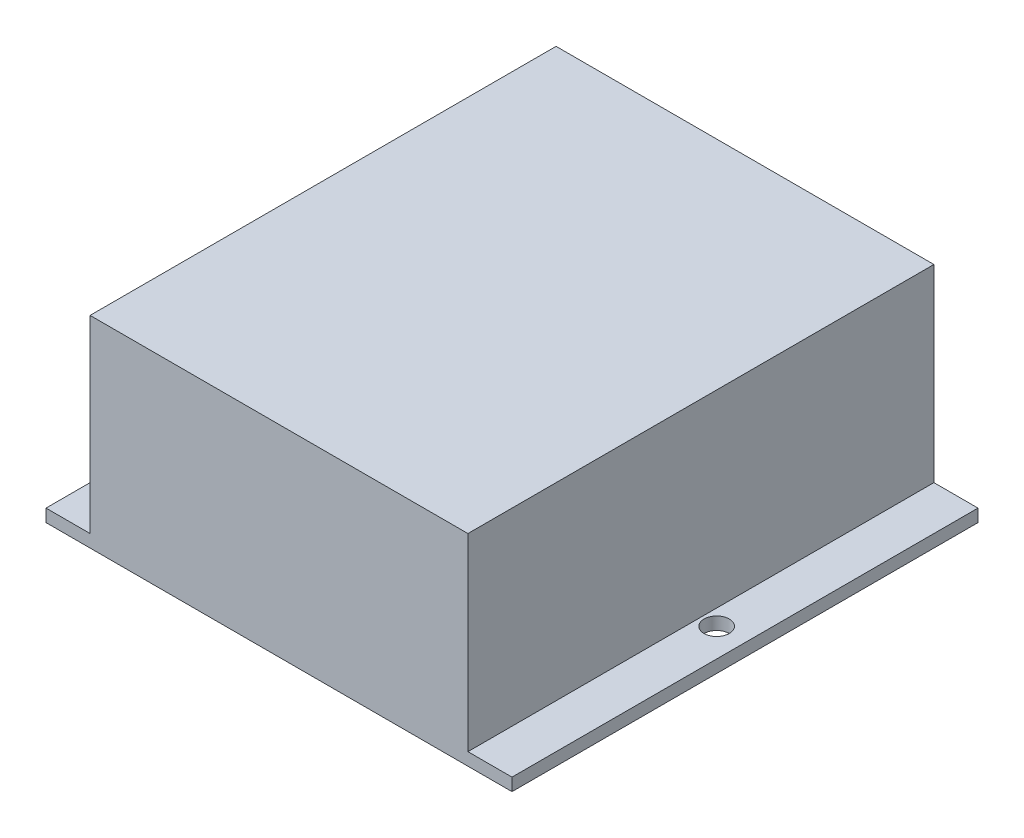
SolidWorks part; units mm, degrees
ref_plane "Front Plane" through (0, 0, 0) normal (0, 0, 1) x (1, 0, 0)
ref_plane "Top Plane" through (0, 0, 0) normal (0, 1, 0) x (1, 0, 0)
ref_plane "Right Plane" through (0, 0, 0) normal (1, 0, 0) x (0, 0, -1)
sketch "Sketch1" plane through (0, 0, 0) normal (0, 1, 0) x (1, 0, 0)
  line L1 (0, 0) -> (74, 0)
  line L2 (0, 0) -> (0, 74)
  line L3 (0, 74) -> (74, 74)
  line L4 (74, 0) -> (74, 74)
  dimension "D1" = 74
  dimension "D2" = 74
extrude "Boss-Extrude1" add sketch "Sketch1" along normal blind 2
sketch "Sketch2" plane through (0, 2, 0) normal (0, 1, 0) x (1, 0, 0)
  line L0 (37, 74) -> (37, 0) construction
  line L1 (74, 74) -> (0, 74) construction
  line L2 (0, 0) -> (74, 0) construction
  line L4 (7, 0) -> (67, 0)
  line L5 (7, 0) -> (7, 74)
  line L6 (7, 74) -> (67, 74)
  line L7 (67, 0) -> (67, 74)
  line L8 (7, 0) -> (67, 74) construction
  line L9 (7, 74) -> (67, 0) construction
  point P6 (37, 37)
  dimension "D1" = 60
extrude "Boss-Extrude2" add sketch "Sketch2" along normal blind 30
sketch "Sketch3" plane through (0, 0, 0) normal (0, -1, 0) x (1, 0, 0)
  line L0 (37, 0) -> (37, -74) construction
  line L1 (0, 0) -> (74, 0) construction
  line L2 (74, -74) -> (0, -74) construction
  line L3 (37, -37) -> (4.5, -37) construction
  line L4 (0, -74) -> (0, 0) construction
  circle A0 centre (4.5, -37) radius 2
  circle A1 centre (69.5, -37) radius 2
  dimension "D1" = 4
  dimension "D2" = 4.5
extrude "Cut-Extrude1" cut sketch "Sketch3" against normal blind 2
